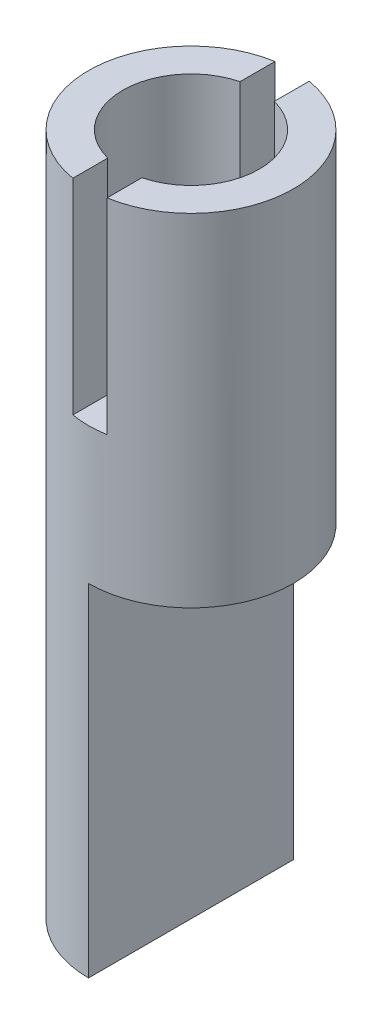
SolidWorks part; units mm, degrees
material "Brass"
ref_plane "Front Plane" through (0, 0, 0) normal (0, 0, 1) x (1, 0, 0)
ref_plane "Top Plane" through (0, 0, 0) normal (0, 1, 0) x (1, 0, 0)
ref_plane "Right Plane" through (0, 0, 0) normal (1, 0, 0) x (0, 0, -1)
sketch "Sketch1" plane through (0, 0, 0) normal (0, 1, 0) x (1, 0, 0)
  circle A0 centre (0, 0) radius 3
  dimension "D1" = 6
extrude "Boss-Extrude1" add sketch "Sketch1" along normal blind 20
sketch "Sketch2" plane through (0, 0, 0) normal (0, -1, 0) x (1, 0, 0)
  line L0 (0, 3) -> (0, -3)
  circle A0 centre (0, 0) radius 3 construction
  arc A1 (0, 3) -> (0, -3) centre (0, 0) cw
extrude "Cut-Extrude1" cut sketch "Sketch2" against normal blind 10
sketch "Sketch3" plane through (0, 20, 0) normal (0, 1, 0) x (1, 0, 0)
  line L0 (-0.5, -1.9365) -> (-0.5, -3.9227)
  line L1 (-0.5, 3.9227) -> (0.5, 3.9227)
  line L2 (-0.5, 3.9227) -> (-0.5, 1.9365)
  line L3 (-0.5, -3.9227) -> (0.5, -3.9227)
  line L4 (0.5, 3.9227) -> (0.5, 1.9365)
  line L5 (-0.5, 3.9227) -> (-0.2529, 1.9839) construction
  line L9 (0.5, -1.9365) -> (0.5, -3.9227)
  arc A0 (0.5, -1.9365) -> (0.5, 1.9365) centre (0, 0) ccw
  arc A1 (-0.5, 1.9365) -> (-0.5, -1.9365) centre (0, 0) ccw
  dimension "D1" = 4
  dimension "D2" = 1
extrude "Cut-Extrude2" cut sketch "Sketch3" against normal blind 6
